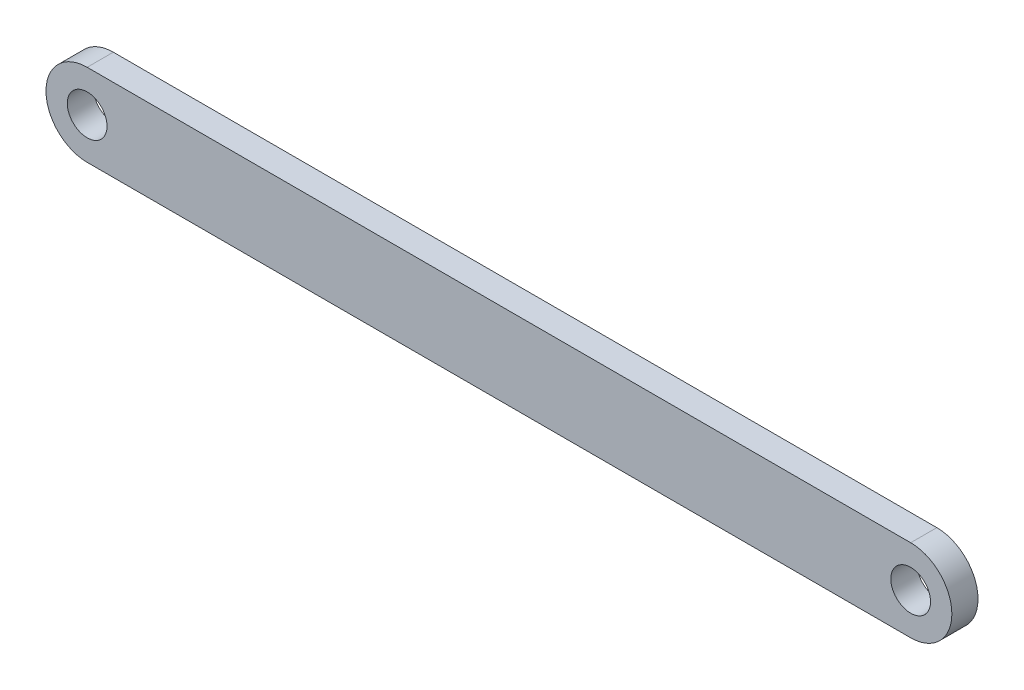
SolidWorks part; units mm, degrees
material "6061 Alloy"
ref_plane "Front Plane" through (0, 0, 0) normal (0, 0, 1) x (1, 0, 0)
ref_plane "Top Plane" through (0, 0, 0) normal (0, 1, 0) x (1, 0, 0)
ref_plane "Right Plane" through (0, 0, 0) normal (1, 0, 0) x (0, 0, -1)
sketch "Sketch1" plane through (0, 0, 0) normal (0, 0, 1) x (1, 0, 0)
  line L0 (-50, 0) -> (50, 0) construction
  line L1 (-50, 5) -> (50, 5)
  line L2 (-50, -5) -> (50, -5)
  arc A0 (-50, 5) -> (-50, -5) centre (-50, 0) ccw
  arc A1 (50, -5) -> (50, 5) centre (50, 0) ccw
  circle A2 centre (-50, 0) radius 2.413
  circle A3 centre (50, 0) radius 2.413
  point P2 (0, 0)
  dimension "D1" = 4.826
  dimension "D2" = 100
  dimension "D3" = 10
extrude "Boss-Extrude1" add sketch "Sketch1" along normal blind 3.175
